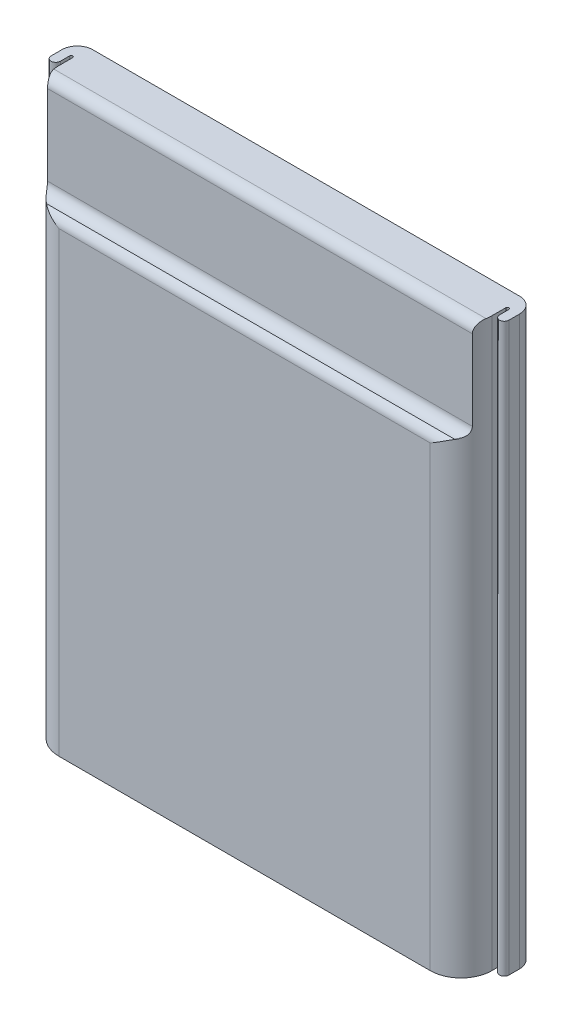
SolidWorks part; units mm, degrees
ref_plane "Front" through (0, 0, 0) normal (0, 0, 1) x (1, 0, 0)
ref_plane "Top" through (0, 0, 0) normal (0, 1, 0) x (1, 0, 0)
ref_plane "Right" through (0, 0, 0) normal (1, 0, 0) x (0, 0, -1)
sketch "Эскиз1" plane through (0, 0, 0) normal (0, 1, 0) x (1, 0, 0)
  line L0 (-13.85, 0) -> (13.85, 0)
  line L1 (-12.05, -4) -> (12.05, -4)
  line L2 (-14.85, -1) -> (-14.85, -1.7)
  line L3 (14.85, -1) -> (14.85, -1.7)
  line L4 (-14.05, -2) -> (-14.05, -1.1)
  line L5 (14.05, -1.1) -> (14.05, -2)
  line L6 (14.25, -1.7) -> (14.25, -1.1)
  line L7 (-14.25, -1.7) -> (-14.25, -1.1)
  arc A0 (-13.85, 0) -> (-14.85, -1) centre (-13.85, -1) ccw
  arc A1 (13.85, 0) -> (14.85, -1) centre (13.85, -1) cw
  arc A2 (-14.05, -2) -> (-12.05, -4) centre (-12.05, -2) ccw
  arc A3 (14.05, -2) -> (12.05, -4) centre (12.05, -2) cw
  arc A4 (14.85, -1.7) -> (14.25, -1.7) centre (14.55, -1.7) cw
  arc A5 (14.05, -1.1) -> (14.25, -1.1) centre (14.15, -1.1) cw
  arc A6 (-14.85, -1.7) -> (-14.25, -1.7) centre (-14.55, -1.7) ccw
  arc A7 (-14.05, -1.1) -> (-14.25, -1.1) centre (-14.15, -1.1) ccw
  point P20 (14.15, -1)
  point P21 (14.55, -2)
  point P27 (-14.15, -1)
  point P28 (-14.55, -2)
  dimension "D1" = 29.7
  dimension "D3" = 2
  dimension "D4" = 1
  dimension "D5" = 0.3
  dimension "D6" = 0.1
  dimension "D2" = 4
extrude "Бобышка-Вытянуть1" add sketch "Эскиз1" along normal mid plane 36.8
sketch "Эскиз2" plane through (0, 0, 0) normal (1, 0, 0) x (0, 0, -1)
  line L0 (-3, 17.75) -> (-3, 12.55)
  line L1 (-3.65, 11.9) -> (-3.35, 11.9)
  line L2 (-4, 18.4) -> (-4, 11.25)
  line L3 (-4, 18.4) -> (-4, -18.4) construction
  line L6 (-4, 18.4) -> (-2.35, 18.4)
  line L7 (0, 18.4) -> (-1, 18.4) construction
  arc A0 (-3, 12.55) -> (-3.65, 11.9) centre (-3.65, 12.55) cw
  arc A1 (-3.35, 11.9) -> (-4, 11.25) centre (-3.35, 11.25) ccw
  arc A2 (-2.35, 18.4) -> (-3, 17.75) centre (-2.35, 17.75) ccw
  dimension "D1" = 0.65
  dimension "D2" = 3
  dimension "D3" = 6.5
extrude "Вырез-Вытянуть1" cut sketch "Эскиз2" against normal up to next and the other way up to next
